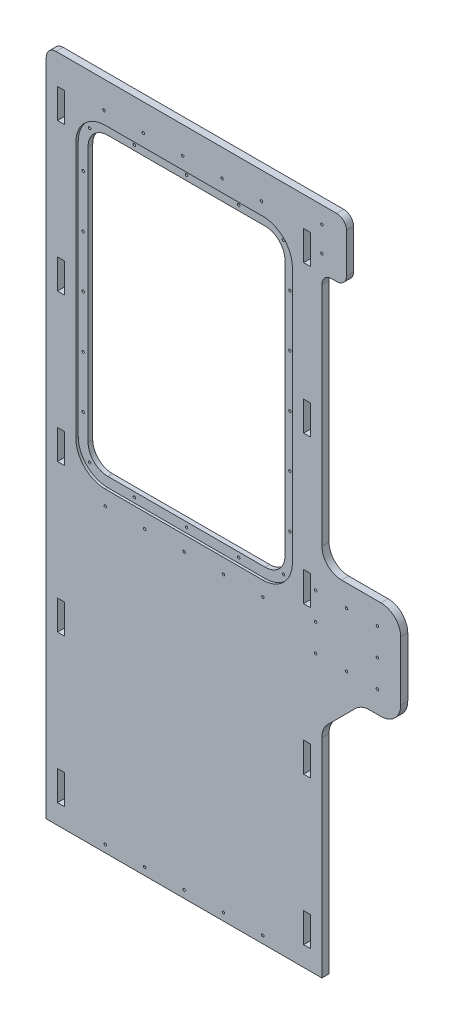
SolidWorks part; units mm, degrees
ref_plane "Front Plane" through (0, 0, 0) normal (0, 0, 1) x (1, 0, 0)
ref_plane "Top Plane" through (0, 0, 0) normal (0, 1, 0) x (1, 0, 0)
ref_plane "Right Plane" through (0, 0, 0) normal (1, 0, 0) x (0, 0, -1)
sketch "Model" plane through (0, 0, 0) normal (0, 0, 1) x (1, 0, 0)
  line L24 (797.921, 645.521) -> (726.079, 573.679)
  line L25 (0, 0) -> (711.2, 0)
  line L26 (0, 0) -> (0, 1701.9397)
  line L27 (25.4, 1727.3397) -> (711.2, 1727.3397)
  line L28 (711.2, 0) -> (711.2, 537.758)
  line L29 (558.8, 838.3397) -> (152.4, 838.3397)
  line L30 (609.6, 889.1397) -> (609.6, 1549.5397)
  line L31 (558.8, 1600.3397) -> (152.4, 1600.3397)
  line L32 (101.6, 889.1397) -> (101.6, 1549.5397)
  line L33 (609.6, 838.3397) -> (101.6, 1600.3397) construction
  line L34 (609.6, 1600.3397) -> (101.6, 838.3397) construction
  line L35 (762, 914.4) -> (863.6, 914.4)
  line L37 (833.842, 660.4) -> (863.6, 660.4)
  line L38 (914.4, 863.6) -> (914.4, 711.2)
  line L39 (711.2, 965.2) -> (711.2, 1549.5397)
  line L41 (711.2, 1727.3397) -> (749.3, 1727.3397)
  line L43 (736.6, 1574.9397) -> (749.3, 1574.9397)
  line L44 (774.7, 1701.9397) -> (774.7, 1600.3397)
  arc A16 (762, 914.4) -> (711.2, 965.2) centre (762, 965.2) cw
  arc A17 (152.4, 838.3397) -> (101.6, 889.1397) centre (152.4, 889.1397) cw
  arc A18 (558.8, 838.3397) -> (609.6, 889.1397) centre (558.8, 889.1397) ccw
  arc A19 (609.6, 1549.5397) -> (558.8, 1600.3397) centre (558.8, 1549.5397) ccw
  arc A20 (152.4, 1600.3397) -> (101.6, 1549.5397) centre (152.4, 1549.5397) ccw
  arc A21 (726.079, 573.679) -> (711.2, 537.758) centre (762, 537.758) ccw
  arc A22 (797.921, 645.521) -> (833.842, 660.4) centre (833.842, 609.6) cw
  arc A23 (863.6, 660.4) -> (914.4, 711.2) centre (863.6, 711.2) ccw
  arc A24 (863.6, 914.4) -> (914.4, 863.6) centre (863.6, 863.6) cw
  arc A25 (749.3, 1727.3397) -> (774.7, 1701.9397) centre (749.3, 1701.9397) cw
  arc A26 (749.3, 1574.9397) -> (774.7, 1600.3397) centre (749.3, 1600.3397) ccw
  arc A27 (711.2, 1549.5397) -> (736.6, 1574.9397) centre (736.6, 1549.5397) cw
  arc A28 (0, 1701.9397) -> (25.4, 1727.3397) centre (25.4, 1701.9397) cw
  point P54 (355.6, 1219.3397)
  point P67 (711.2, 914.4)
  point P89 (914.4, 660.4)
  point P92 (914.4, 914.4)
  point P95 (774.7, 1727.3397)
  point P99 (774.7, 1574.9397)
  point P104 (0, 1727.3397)
  dimension "D31" = 50.8
  dimension "D36" = 50.8
  dimension "D39" = 50.8
  dimension "D40" = 50.8
  dimension "D41" = 25.4
  dimension "D42" = 25.4
  dimension "D1" = 0
  dimension "D5" = 0
  dimension "D6" = 711.2
  dimension "D7" = 584.3397
  dimension "D8" = 101.6
  dimension "D26" = 711.2
  dimension "D27" = 914.4
  dimension "D28" = 203.2
  dimension "D29" = 254
  dimension "D30" = 45
  dimension "D32" = 152.4
  dimension "D33" = 63.5
  dimension "D34" = 508
  dimension "D35" = 762
  dimension "D37" = 127
  dimension "D38" = 355.6
other "AlignGroup1"
other "AlignGroup2"
other "AlignGroup3"
other "AlignGroup4"
other "AlignGroup5"
other "AlignGroup6"
extrude "Boss-Extrude1" add sketch "Model" along normal blind 18.288
sketch "Sketch1" plane through (0, 0, 18.288) normal (0, 0, 1) x (1, 0, 0)
  line L1 (663.956, 127) -> (682.244, 127)
  line L2 (663.956, 127) -> (663.956, 50.8)
  line L3 (663.956, 50.8) -> (682.244, 50.8)
  line L4 (682.244, 127) -> (682.244, 50.8)
  line L6 (0, 0) -> (711.2, 0) construction
  line L7 (711.2, 0) -> (711.2, 537.758) construction
  line L8 (0, 1701.9397) -> (0, 0) construction
  line L9 (47.244, 127) -> (28.956, 127)
  line L10 (47.244, 127) -> (47.244, 50.8)
  line L11 (47.244, 50.8) -> (28.956, 50.8)
  line L12 (28.956, 127) -> (28.956, 50.8)
  point P6 (673.1, 50.8)
  point P13 (38.1, 50.8)
  dimension "D1" = 18.288
  dimension "D2" = 38.1
  dimension "D3" = 50.8
  dimension "D4" = 76.2
  dimension "D5" = 38.1
extrude "Mortise cuts" cut sketch "Sketch1" against normal through all
pattern_linear "LPattern1" count 5 spacing 381 along (0, 1, 0) of "Mortise cuts"
sketch "Sketch2" plane through (0, 0, 18.288) normal (0, 0, 1) x (1, 0, 0)
  line L24 (635, 889.1397) -> (635, 1549.5397)
  line L25 (152.4, 812.9397) -> (558.8, 812.9397)
  line L26 (76.2, 1549.5397) -> (76.2, 889.1397)
  line L27 (558.8, 1625.7397) -> (152.4, 1625.7397)
  line L28 (635, 889.1397) -> (635, 1549.5397)
  line L29 (152.4, 812.9397) -> (558.8, 812.9397)
  line L30 (76.2, 1549.5397) -> (76.2, 889.1397)
  line L31 (558.8, 1625.7397) -> (152.4, 1625.7397)
  arc A20 (635, 1549.5397) -> (558.8, 1625.7397) centre (558.8, 1549.5397) ccw
  arc A21 (558.8, 812.9397) -> (635, 889.1397) centre (558.8, 889.1397) ccw
  arc A22 (76.2, 889.1397) -> (152.4, 812.9397) centre (152.4, 889.1397) ccw
  arc A23 (152.4, 1625.7397) -> (76.2, 1549.5397) centre (152.4, 1549.5397) ccw
  arc A24 (635, 1549.5397) -> (558.8, 1625.7397) centre (558.8, 1549.5397) ccw
  arc A25 (558.8, 812.9397) -> (635, 889.1397) centre (558.8, 889.1397) ccw
  arc A26 (76.2, 889.1397) -> (152.4, 812.9397) centre (152.4, 889.1397) ccw
  arc A27 (152.4, 1625.7397) -> (76.2, 1549.5397) centre (152.4, 1549.5397) ccw
  dimension "D1" = 25.4
extrude "Window Recess" cut sketch "Sketch2" against normal blind 6.35
sketch "Sketch3" plane through (0, 0, 11.938) normal (0, 0, 1) x (1, 0, 0)
  line L0 (355.6, 1625.7397) -> (355.6, 812.9397) construction
  line L1 (558.8, 1625.7397) -> (152.4, 1625.7397) construction
  line L2 (152.4, 812.9397) -> (558.8, 812.9397) construction
  line L3 (76.2, 1219.3397) -> (635, 1219.3397) construction
  line L4 (76.2, 1549.5397) -> (76.2, 889.1397) construction
  line L5 (635, 889.1397) -> (635, 1549.5397) construction
  line L6 (98.5185, 1603.4213) -> (612.6815, 835.2582) construction
  line L7 (612.6815, 1603.4213) -> (98.5185, 835.2582) construction
  arc A0 (152.4, 1625.7397) -> (76.2, 1549.5397) centre (152.4, 1549.5397) ccw construction
  arc A1 (558.8, 812.9397) -> (635, 889.1397) centre (558.8, 889.1397) ccw construction
  arc A2 (635, 1549.5397) -> (558.8, 1625.7397) centre (558.8, 1549.5397) ccw construction
  arc A3 (76.2, 889.1397) -> (152.4, 812.9397) centre (152.4, 889.1397) ccw construction
  circle A4 centre (105.5827, 1592.8673) radius 3.175
  circle A5 centre (605.6173, 1592.8673) radius 3.175
  circle A7 centre (605.6173, 845.8122) radius 3.175
  circle A8 centre (105.5827, 845.8122) radius 3.175
  dimension "D1" = 12.7
  dimension "D4" = 12.7
  dimension "D5" = 6.35
  dimension "D6" = 12.7
  dimension "D7" = 12.7
extrude "Cut-Extrude4" cut sketch "Sketch3" against normal through all
sketch "Sketch6" plane through (0, 0, 11.938) normal (0, 0, 1) x (1, 0, 0)
  line L0 (76.2, 1219.3397) -> (635, 1219.3397) construction
  line L1 (76.2, 1549.5397) -> (76.2, 889.1397) construction
  circle A0 centre (88.9, 1219.3397) radius 3.175
  dimension "D1" = 12.7
extrude "Cut-Extrude5" cut sketch "Sketch6" against normal through all
pattern_linear "LPattern2" count 3 spacing 134.62 along (0, -1, 0) count 3 spacing 134.62 along (0, 1, 0) of "Cut-Extrude5"
ref_plane "Plane1" through (355.6, 0, 0) normal (-1, 0, 0) x (0, 0, 1)
mirror "Mirror1" about plane through (355.6, 0, 0) normal (-1, 0, 0) of "LPattern2", "Cut-Extrude5"
sketch "Sketch7" plane through (0, 0, 11.938) normal (0, 0, 1) x (1, 0, 0)
  line L0 (355.6, 1625.7397) -> (355.6, 812.9397) construction
  line L1 (558.8, 1625.7397) -> (152.4, 1625.7397) construction
  circle A0 centre (355.6, 1613.0397) radius 3.175
  dimension "D1" = 12.7
extrude "Cut-Extrude6" cut sketch "Sketch7" against normal through all
pattern_linear "LPattern3" count 2 spacing 134.62 along (1, 0, 0) count 2 spacing 134.62 along (-1, 0, 0) of "Cut-Extrude6"
ref_plane "Plane2" through (0, 1219.3397, 0) normal (0, -1, 0) x (-1, 0, 0)
mirror "Mirror2" about plane through (0, 1219.3397, 0) normal (0, -1, 0) of "LPattern3", "Cut-Extrude6"
sketch "Sketch8" plane through (0, 0, 18.288) normal (0, 0, 1) x (1, 0, 0)
  line L0 (0, 1701.9397) -> (0, 0) construction
  line L1 (609.6, 755.65) -> (101.6, 755.65) construction
  line L2 (609.6, 755.65) -> (609.6, 793.75) construction
  line L3 (609.6, 793.75) -> (101.6, 793.75) construction
  line L4 (101.6, 755.65) -> (101.6, 793.75) construction
  line L5 (609.6, 755.65) -> (101.6, 793.75) construction
  line L6 (609.6, 793.75) -> (101.6, 755.65) construction
  line L7 (609.6, 0) -> (101.6, 0) construction
  line L8 (609.6, 38.1) -> (101.6, 38.1) construction
  line L9 (101.6, 0) -> (101.6, 38.1) construction
  line L10 (609.6, 0) -> (609.6, 38.1) construction
  line L11 (0, 0) -> (711.2, 0) construction
  circle A0 centre (558.8, 774.7) radius 3.175
  circle A1 centre (457.2, 774.7) radius 3.175
  circle A2 centre (355.6, 774.7) radius 3.175
  circle A3 centre (254, 774.7) radius 3.175
  circle A4 centre (152.4, 774.7) radius 3.175
  circle A10 centre (558.8, 19.05) radius 3.175
  circle A11 centre (457.2, 19.05) radius 3.175
  circle A12 centre (355.6, 19.05) radius 3.175
  circle A13 centre (254, 19.05) radius 3.175
  circle A14 centre (152.4, 19.05) radius 3.175
  point P0 (355.6, 774.7)
  dimension "D3" = 6.35
  dimension "D4" = 50.8
  dimension "D6" = 355.6
  dimension "D9" = 0
  dimension "D1" = 38.1
  dimension "D2" = 508
  dimension "D8" = 774.7
  dimension "D5" = 5
  dimension "D7" = 2
extrude "Cut-Extrude7" cut sketch "Sketch8" against normal through all
sketch "Sketch9" plane through (0, 0, 0) normal (0, 0, -1) x (-1, 0, 0)
  circle A0 centre (-774.7, 858.012) radius 3.175
  circle A1 centre (-854.456, 858.012) radius 3.175
  circle A2 centre (-694.944, 858.012) radius 3.175
  circle A3 centre (-694.944, 787.4) radius 3.175
  circle A4 centre (-694.944, 716.788) radius 3.175
  circle A5 centre (-774.7, 716.788) radius 3.175
  circle A6 centre (-854.456, 716.788) radius 3.175
  circle A7 centre (-854.456, 787.4) radius 3.175
extrude "Cut-Extrude8" cut sketch "Sketch9" against normal through all
sketch "Sketch10" plane through (0, 0, 0) normal (0, 0, -1) x (-1, 0, 0)
  circle A0 centre (-555.244, 1657.4897) radius 3.175
  circle A1 centre (-453.644, 1657.4897) radius 3.175
  circle A2 centre (-352.044, 1657.4897) radius 3.175
  circle A3 centre (-250.444, 1657.4897) radius 3.175
  circle A4 centre (-148.844, 1657.4897) radius 3.175
  dimension "D1" = 5
extrude "Cut-Extrude9" cut sketch "Sketch10" against normal through all
sketch "Sketch11" plane through (0, 0, 0) normal (0, 0, -1) x (-1, 0, 0)
  circle A0 centre (-711.2, 1683.549) radius 3.175
  circle A1 centre (-711.2, 1618.525) radius 3.175
extrude "Cut-Extrude10" cut sketch "Sketch11" against normal through all
